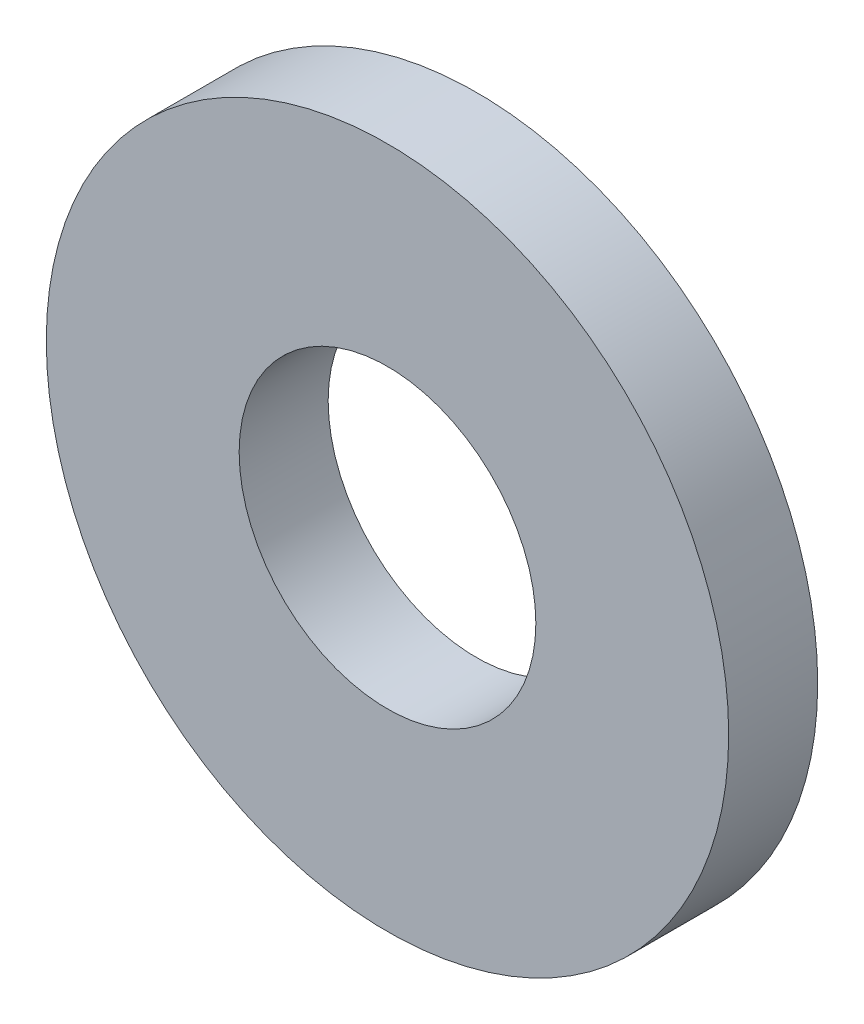
SolidWorks part; units mm, degrees
ref_plane "前视基准面" through (0, 0, 0) normal (0, 0, 1) x (1, 0, 0)
ref_plane "上视基准面" through (0, 0, 0) normal (0, 1, 0) x (1, 0, 0)
ref_plane "右视基准面" through (0, 0, 0) normal (1, 0, 0) x (0, 0, -1)
sketch "草图1" plane through (0, 0, 0) normal (0, 0, 1) x (1, 0, 0)
  line L0 (55, 0) -> (-55, 0) construction
  line L1 (0, -55) -> (0, 55) construction
  circle A0 centre (0, 0) radius 11.5
  circle A1 centre (0, 0) radius 8 construction
  circle A2 centre (0, 8) radius 2.65
  circle A3 centre (8, 0) radius 2.65
  circle A4 centre (0, -8) radius 2.65
  circle A5 centre (-8, 0) radius 2.65
extrude "凸台-拉伸1" add sketch "草图1" along normal blind 2
sketch "草图2" plane through (0, 0, 2) normal (0, 0, 1) x (1, 0, 0)
  circle A0 centre (0, 0) radius 11.5
extrude "凸台-拉伸2" add sketch "草图2" along normal blind 1
sketch "草图3" plane through (0, 0, 3) normal (0, 0, 1) x (1, 0, 0)
  circle A0 centre (0, 0) radius 5
extrude "切除-拉伸1" cut sketch "草图3" against normal blind 10
